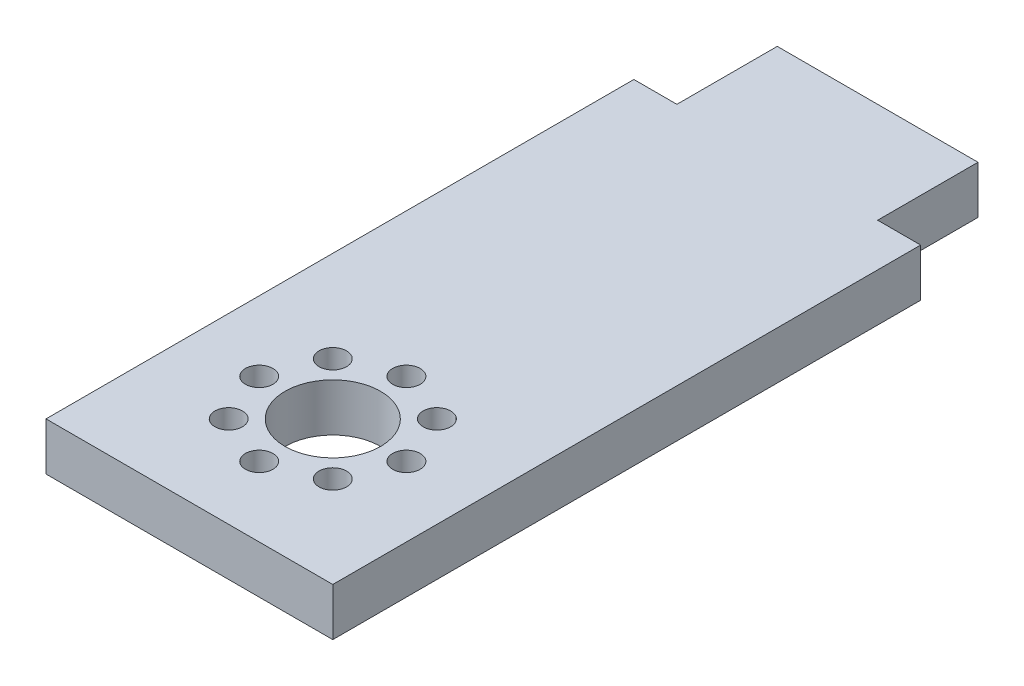
SolidWorks part; units mm, degrees
ref_plane "Front Plane" through (0, 0, 0) normal (0, 0, 1) x (1, 0, 0)
ref_plane "Top Plane" through (0, 0, 0) normal (0, 1, 0) x (1, 0, 0)
ref_plane "Right Plane" through (0, 0, 0) normal (1, 0, 0) x (0, 0, -1)
sketch "Sketch1" plane through (0, 0, 0) normal (0, 1, 0) x (1, 0, 0)
  line L0 (-35.0645, 47.3622) -> (-35.0645, 7.3632)
  line L1 (-35.0645, 7.3632) -> (-35.0645, -30.7368)
  line L2 (-35.0645, -30.7368) -> (3.0355, -30.7368)
  line L3 (3.0355, -30.7368) -> (3.0355, 7.3632)
  line L4 (3.0355, 7.3632) -> (3.0355, 47.3622)
  line L5 (3.0355, 47.3622) -> (-35.0645, 47.3622)
  line L6 (-16.0145, 47.3622) -> (-16.0145, -30.7368) construction
  line L7 (-28.0001, -11.6868) -> (0, -11.6868) construction
  circle A0 centre (-16.0145, -11.6868) radius 6.35
  circle A1 centre (-16.0145, -21.4658) radius 1.8288
  circle A2 centre (-22.9293, -18.6016) radius 1.8288
  circle A3 centre (-25.7935, -11.6868) radius 1.8288
  circle A4 centre (-22.9293, -4.772) radius 1.8288
  circle A5 centre (-16.0145, -1.9078) radius 1.8288
  circle A6 centre (-9.0997, -4.772) radius 1.8288
  circle A7 centre (-6.2355, -11.6868) radius 1.8288
  circle A8 centre (-9.0997, -18.6016) radius 1.8288
  point P31 (-16.0145, -11.6868)
  dimension "D5" = 12.7
  dimension "D8" = 3.6576
  dimension "D1" = 39.999
  dimension "D2" = 39.999
  dimension "D3" = 38.1
  dimension "D4" = 38.1
  dimension "D6" = 19.05
  dimension "D7" = 9.779
  dimension "D9" = 8
extrude "Boss-Extrude1" add sketch "Sketch1" along normal blind 6.35
sketch "Sketch2" plane through (0, 6.35, 0) normal (0, 1, 0) x (1, 0, 0)
  line L0 (-16.0145, 47.3622) -> (-16.0145, -30.7368) construction
  line L1 (3.0355, 47.3622) -> (-35.0645, 47.3622) construction
  line L2 (-35.0645, -30.7368) -> (3.0355, -30.7368) construction
  line L4 (-29.348, 60.6957) -> (-2.681, 60.6957)
  line L5 (-29.348, 60.6957) -> (-29.348, 34.0287)
  line L6 (-29.348, 34.0287) -> (-2.681, 34.0287)
  line L7 (-2.681, 60.6957) -> (-2.681, 34.0287)
  line L8 (-29.348, 60.6957) -> (-2.681, 34.0287) construction
  line L9 (-29.348, 34.0287) -> (-2.681, 60.6957) construction
  dimension "D1" = 26.667
  dimension "D2" = 26.667
extrude "Boss-Extrude2" add sketch "Sketch2" against normal blind 6.35
